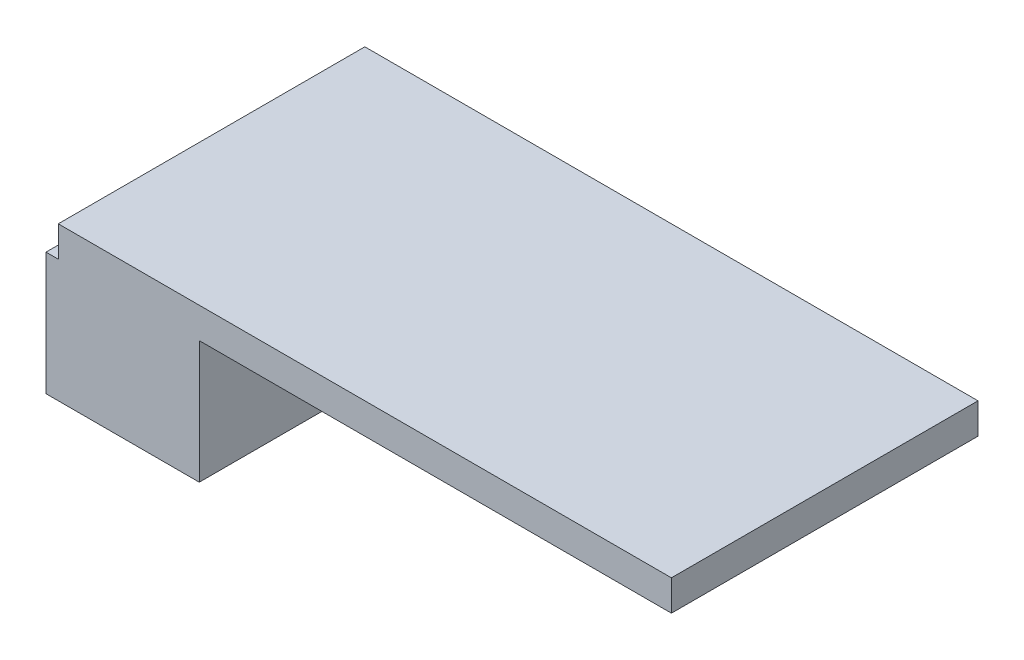
SolidWorks part; units mm, degrees
ref_plane "Front Plane" through (0, 0, 0) normal (0, 0, 1) x (1, 0, 0)
ref_plane "Top Plane" through (0, 0, 0) normal (0, 1, 0) x (1, 0, 0)
ref_plane "Right Plane" through (0, 0, 0) normal (1, 0, 0) x (0, 0, -1)
sketch "Sketch1" plane through (0, 0, 0) normal (0, 1, 0) x (1, 0, 0)
  line L1 (0, 0) -> (100, 0)
  line L2 (0, 0) -> (0, 50)
  line L3 (0, 50) -> (100, 50)
  line L4 (100, 0) -> (100, 50)
  dimension "D1" = 50
  dimension "D2" = 100
extrude "Boss-Extrude1" add sketch "Sketch1" along normal blind 5
sketch "Sketch2" plane through (0, 0, 0) normal (0, -1, 0) x (1, 0, 0)
  line L0 (100, -50) -> (0, -50) construction
  line L1 (-2, 0) -> (23, 0)
  line L2 (-2, 0) -> (-2, -50)
  line L3 (-2, -50) -> (23, -50)
  line L4 (23, 0) -> (23, -50)
  line L7 (0, -50) -> (0, 0) construction
  dimension "D1" = 50
  dimension "D2" = 25
  dimension "D3" = 2
extrude "Boss-Extrude2" add sketch "Sketch2" along normal blind 20
sketch "Sketch3" plane through (0, 0, 0) normal (0, -1, 0) x (1, 0, 0)
  line L1 (55.8545, -7) -> (68.8545, -7)
  line L2 (55.8545, -7) -> (55.8545, -20)
  line L3 (55.8545, -20) -> (68.8545, -20)
  line L4 (68.8545, -7) -> (68.8545, -20)
  line L5 (48.8545, -25) -> (68.8545, -25)
  line L6 (48.8545, -25) -> (48.8545, -45)
  line L7 (48.8545, -45) -> (68.8545, -45)
  line L8 (68.8545, -25) -> (68.8545, -45)
  line L9 (39, -42.5) -> (43.5, -42.5)
  line L10 (39, -42.5) -> (39, -47)
  line L11 (39, -47) -> (43.5, -47)
  line L12 (43.5, -42.5) -> (43.5, -47)
  line L29 (35.7303, -33.9833) -> (36.7303, -33.9833)
  line L30 (35.7303, -33.9833) -> (35.7303, -36.4833)
  line L31 (35.7303, -36.4833) -> (36.7303, -36.4833)
  line L32 (36.7303, -33.9833) -> (36.7303, -36.4833)
  line L48 (72.8545, 0) -> (72.8545, -50) construction
  line L49 (81.8545, -12) -> (87.8545, -12)
  line L50 (81.8545, -12) -> (81.8545, -18)
  line L51 (81.8545, -18) -> (87.8545, -18)
  line L52 (87.8545, -12) -> (87.8545, -18)
  line L53 (23, 0) -> (100, 0) construction
  line L54 (100, -50) -> (23, -50) construction
  line L55 (81.8545, -21) -> (87.8545, -21)
  line L56 (81.8545, -21) -> (81.8545, -27)
  line L57 (81.8545, -27) -> (87.8545, -27)
  line L58 (87.8545, -21) -> (87.8545, -27)
  line L59 (81.8545, -30) -> (87.8545, -30)
  line L60 (81.8545, -30) -> (81.8545, -36)
  line L61 (81.8545, -36) -> (87.8545, -36)
  line L62 (87.8545, -30) -> (87.8545, -36)
  line L63 (81.8545, -39) -> (87.8545, -39)
  line L64 (81.8545, -39) -> (81.8545, -45)
  line L65 (81.8545, -45) -> (87.8545, -45)
  line L66 (87.8545, -39) -> (87.8545, -45)
  line L67 (32.5, -42.5) -> (37, -42.5)
  line L68 (32.5, -42.5) -> (32.5, -47)
  line L69 (32.5, -47) -> (37, -47)
  line L70 (37, -42.5) -> (37, -47)
  line L71 (26, -42.5) -> (30.5, -42.5)
  line L72 (26, -42.5) -> (26, -47)
  line L73 (26, -47) -> (30.5, -47)
  line L74 (30.5, -42.5) -> (30.5, -47)
  line L75 (23, -50) -> (23, 0) construction
  line L76 (38, -34) -> (42.5, -34)
  line L77 (38, -34) -> (38, -38.5)
  line L78 (38, -38.5) -> (42.5, -38.5)
  line L79 (42.5, -34) -> (42.5, -38.5)
  line L84 (26, -34) -> (30.5, -34)
  line L85 (26, -34) -> (26, -38.5)
  line L86 (26, -38.5) -> (30.5, -38.5)
  line L87 (30.5, -34) -> (30.5, -38.5)
  line L88 (33.5568, -34.0031) -> (34.5568, -34.0031)
  line L89 (33.5568, -34.0031) -> (33.5568, -36.5031)
  line L90 (33.5568, -36.5031) -> (34.5568, -36.5031)
  line L91 (34.5568, -34.0031) -> (34.5568, -36.5031)
  line L92 (31.6692, -33.9674) -> (32.6692, -33.9674)
  line L93 (31.6692, -33.9674) -> (31.6692, -36.4674)
  line L94 (31.6692, -36.4674) -> (32.6692, -36.4674)
  line L95 (32.6692, -33.9674) -> (32.6692, -36.4674)
  line L96 (38.388, -29.6867) -> (39.388, -29.6867)
  line L97 (38.388, -29.6867) -> (38.388, -32.1867)
  line L98 (38.388, -32.1867) -> (39.388, -32.1867)
  line L99 (39.388, -29.6867) -> (39.388, -32.1867)
  line L100 (40.0255, -29.6746) -> (41.0255, -29.6746)
  line L101 (40.0255, -29.6746) -> (40.0255, -32.1746)
  line L102 (40.0255, -32.1746) -> (41.0255, -32.1746)
  line L103 (41.0255, -29.6746) -> (41.0255, -32.1746)
  line L104 (50.2838, -46.1568) -> (51.2838, -46.1568)
  line L105 (50.2838, -46.1568) -> (50.2838, -48.6568)
  line L106 (50.2838, -48.6568) -> (51.2838, -48.6568)
  line L107 (51.2838, -46.1568) -> (51.2838, -48.6568)
  line L108 (51.7634, -46.2286) -> (52.7634, -46.2286)
  line L109 (51.7634, -46.2286) -> (51.7634, -48.7286)
  line L110 (51.7634, -48.7286) -> (52.7634, -48.7286)
  line L111 (52.7634, -46.2286) -> (52.7634, -48.7286)
  line L112 (54.0586, -46.1363) -> (55.0586, -46.1363)
  line L113 (54.0586, -46.1363) -> (54.0586, -48.6363)
  line L114 (54.0586, -48.6363) -> (55.0586, -48.6363)
  line L115 (55.0586, -46.1363) -> (55.0586, -48.6363)
  line L116 (55.8744, -46.2244) -> (56.8744, -46.2244)
  line L117 (55.8744, -46.2244) -> (55.8744, -48.7244)
  line L118 (55.8744, -48.7244) -> (56.8744, -48.7244)
  line L119 (56.8744, -46.2244) -> (56.8744, -48.7244)
  line L120 (58.2926, -46.4096) -> (59.2926, -46.4096)
  line L121 (58.2926, -46.4096) -> (58.2926, -48.9096)
  line L122 (58.2926, -48.9096) -> (59.2926, -48.9096)
  line L123 (59.2926, -46.4096) -> (59.2926, -48.9096)
  line L124 (60.7252, -46.2562) -> (61.7252, -46.2562)
  line L125 (60.7252, -46.2562) -> (60.7252, -48.7562)
  line L126 (60.7252, -48.7562) -> (61.7252, -48.7562)
  line L127 (61.7252, -46.2562) -> (61.7252, -48.7562)
  line L128 (62.81, -46.3574) -> (63.81, -46.3574)
  line L129 (62.81, -46.3574) -> (62.81, -48.8574)
  line L130 (62.81, -48.8574) -> (63.81, -48.8574)
  line L131 (63.81, -46.3574) -> (63.81, -48.8574)
  line L132 (64.6931, -46.4487) -> (65.6931, -46.4487)
  line L133 (64.6931, -46.4487) -> (64.6931, -48.9487)
  line L134 (64.6931, -48.9487) -> (65.6931, -48.9487)
  line L135 (65.6931, -46.4487) -> (65.6931, -48.9487)
  line L136 (67.1958, -46.2308) -> (68.1958, -46.2308)
  line L137 (67.1958, -46.2308) -> (67.1958, -48.7308)
  line L138 (67.1958, -48.7308) -> (68.1958, -48.7308)
  line L139 (68.1958, -46.2308) -> (68.1958, -48.7308)
  line L140 (51.1201, -20.9188) -> (52.1201, -20.9188)
  line L141 (51.1201, -20.9188) -> (51.1201, -23.4188)
  line L142 (51.1201, -23.4188) -> (52.1201, -23.4188)
  line L143 (52.1201, -20.9188) -> (52.1201, -23.4188)
  line L144 (54.3281, -20.9188) -> (55.3281, -20.9188)
  line L145 (54.3281, -20.9188) -> (54.3281, -23.4188)
  line L146 (54.3281, -23.4188) -> (55.3281, -23.4188)
  line L147 (55.3281, -20.9188) -> (55.3281, -23.4188)
  line L148 (57.1219, -20.9188) -> (58.1219, -20.9188)
  line L149 (57.1219, -20.9188) -> (57.1219, -23.4188)
  line L150 (57.1219, -23.4188) -> (58.1219, -23.4188)
  line L151 (58.1219, -20.9188) -> (58.1219, -23.4188)
  line L152 (59.6825, -20.9188) -> (60.6825, -20.9188)
  line L153 (59.6825, -20.9188) -> (59.6825, -23.4188)
  line L154 (59.6825, -23.4188) -> (60.6825, -23.4188)
  line L155 (60.6825, -20.9188) -> (60.6825, -23.4188)
  line L156 (63.6187, -20.9188) -> (64.6187, -20.9188)
  line L157 (63.6187, -20.9188) -> (63.6187, -23.4188)
  line L158 (63.6187, -23.4188) -> (64.6187, -23.4188)
  line L159 (64.6187, -20.9188) -> (64.6187, -23.4188)
  line L160 (61.8145, -20.9188) -> (62.8145, -20.9188)
  line L161 (61.8145, -20.9188) -> (61.8145, -23.4188)
  line L162 (61.8145, -23.4188) -> (62.8145, -23.4188)
  line L163 (62.8145, -20.9188) -> (62.8145, -23.4188)
  line L164 (66.5017, -20.9188) -> (67.5017, -20.9188)
  line L165 (66.5017, -20.9188) -> (66.5017, -23.4188)
  line L166 (66.5017, -23.4188) -> (67.5017, -23.4188)
  line L167 (67.5017, -20.9188) -> (67.5017, -23.4188)
  line L168 (57.7631, -2.013) -> (58.7631, -2.013)
  line L169 (57.7631, -2.013) -> (57.7631, -4.513)
  line L170 (57.7631, -4.513) -> (58.7631, -4.513)
  line L171 (58.7631, -2.013) -> (58.7631, -4.513)
  line L172 (60.1181, -2.013) -> (61.1181, -2.013)
  line L173 (60.1181, -2.013) -> (60.1181, -4.513)
  line L174 (60.1181, -4.513) -> (61.1181, -4.513)
  line L175 (61.1181, -2.013) -> (61.1181, -4.513)
  line L176 (62.3902, -2.013) -> (63.3902, -2.013)
  line L177 (62.3902, -2.013) -> (62.3902, -4.513)
  line L178 (62.3902, -4.513) -> (63.3902, -4.513)
  line L179 (63.3902, -2.013) -> (63.3902, -4.513)
  line L180 (64.8952, -2.013) -> (65.8952, -2.013)
  line L181 (64.8952, -2.013) -> (64.8952, -4.513)
  line L182 (64.8952, -4.513) -> (65.8952, -4.513)
  line L183 (65.8952, -2.013) -> (65.8952, -4.513)
  line L184 (66.2602, -2.013) -> (67.2602, -2.013)
  line L185 (66.2602, -2.013) -> (66.2602, -4.513)
  line L186 (66.2602, -4.513) -> (67.2602, -4.513)
  line L187 (67.2602, -2.013) -> (67.2602, -4.513)
  line L188 (55.8545, -2.013) -> (68.0602, -2.013) construction
  line L189 (50.4981, -20.9188) -> (68.0602, -20.9188) construction
  point P18 (68.8545, -35)
  dimension "D1" = 4.5
  dimension "D2" = 4.5
  dimension "D3" = 2.5
  dimension "D4" = 1
  dimension "D5" = 13
  dimension "D6" = 13
  dimension "D7" = 20
  dimension "D8" = 20
  dimension "D9" = 6
  dimension "D10" = 6
  dimension "D11" = 4
  dimension "D12" = 4
  dimension "D13" = 5
  dimension "D14" = 5
  dimension "D15" = 9
  dimension "D16" = 12
  dimension "D17" = 6
  dimension "D18" = 6
  dimension "D19" = 6
  dimension "D20" = 6
  dimension "D21" = 6
  dimension "D22" = 6
  dimension "D23" = 3
  dimension "D24" = 3
  dimension "D25" = 3
  dimension "D26" = 9
  dimension "D27" = 9
  dimension "D28" = 9
  dimension "D29" = 3
  dimension "D30" = 3
  dimension "D31" = 4.5
  dimension "D32" = 4.5
  dimension "D33" = 4.5
  dimension "D34" = 4.5
  dimension "D35" = 2
  dimension "D36" = 2
  dimension "D37" = 3
  dimension "D38" = 3
  dimension "D39" = 4.5
  dimension "D40" = 4.5
  dimension "D41" = 4.5
  dimension "D42" = 4.5
  dimension "D43" = 3
  dimension "D44" = 7.5
  dimension "D45" = 4
  dimension "D46" = 4
extrude "Boss-Extrude3" add sketch "Sketch3" along normal blind 2
sketch "Sketch4" plane through (0, 0, 0) normal (0, -1, 0) x (1, 0, 0)
  line L0 (23, 0) -> (100, 0) construction
  line L1 (72.5721, -5) -> (79.5721, -5)
  line L2 (72.5721, -5) -> (72.5721, -45)
  line L3 (72.5721, -45) -> (79.5721, -45)
  line L4 (79.5721, -5) -> (79.5721, -45)
  dimension "D1" = 5
  dimension "D2" = 40
  dimension "D3" = 7
extrude "Boss-Extrude4" add sketch "Sketch4" along normal blind 5
